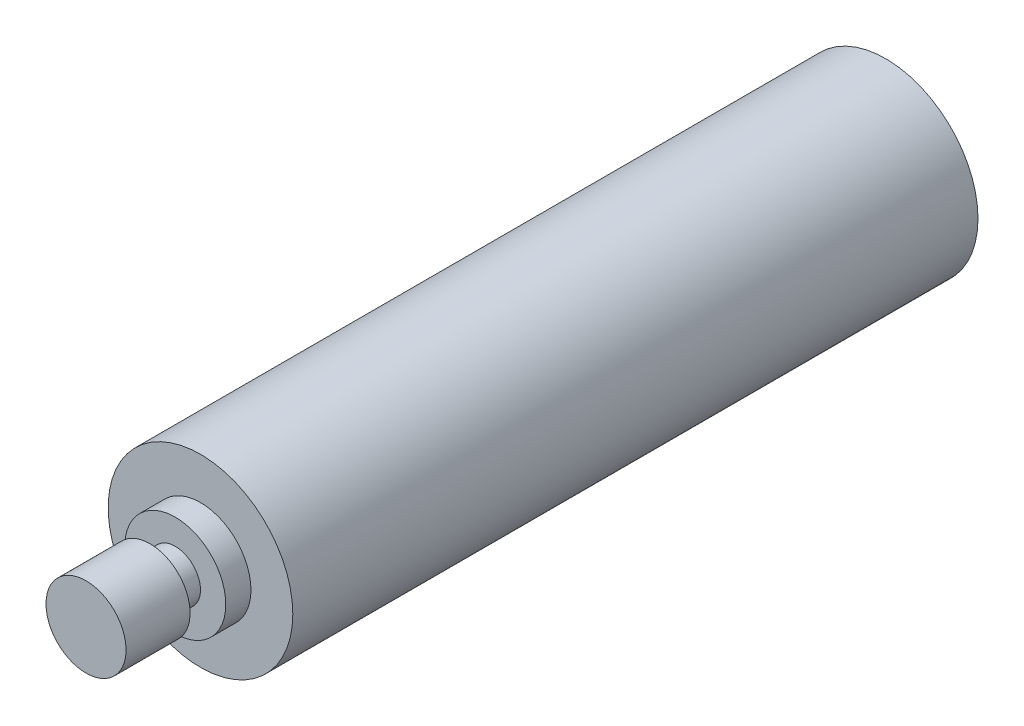
SolidWorks part; units mm, degrees
material "Copper"
ref_plane "Front Plane" through (0, 0, 0) normal (0, 0, 1) x (1, 0, 0)
ref_plane "Top Plane" through (0, 0, 0) normal (0, 1, 0) x (1, 0, 0)
ref_plane "Right Plane" through (0, 0, 0) normal (1, 0, 0) x (0, 0, -1)
sketch "Sketch1" plane through (0, 0, 0) normal (0, 0, 1) x (1, 0, 0)
  circle A0 centre (0, 0) radius 10.9855
  dimension "D1" = 21.971
extrude "Boss-Extrude1" add sketch "Sketch1" along normal blind 81.534
sketch "Sketch2" plane through (0, 0, 81.534) normal (0, 0, 1) x (1, 0, 0)
  circle A0 centre (0, 0) radius 6.0071
  dimension "D1" = 12.0142
extrude "Boss-Extrude2" add sketch "Sketch2" along normal blind 3
sketch "Sketch3" plane through (0, 0, 84.534) normal (0, 0, 1) x (1, 0, 0)
  circle A0 centre (0, 0) radius 2.9972
  dimension "D1" = 5.9944
extrude "Boss-Extrude3" add sketch "Sketch3" along normal blind 3
sketch "Sketch4" plane through (0, 0, 87.534) normal (0, 0, 1) x (1, 0, 0)
  circle A0 centre (0, 0) radius 4.7625
  dimension "D1" = 9.525
extrude "Boss-Extrude4" add sketch "Sketch4" along normal blind 7.62
